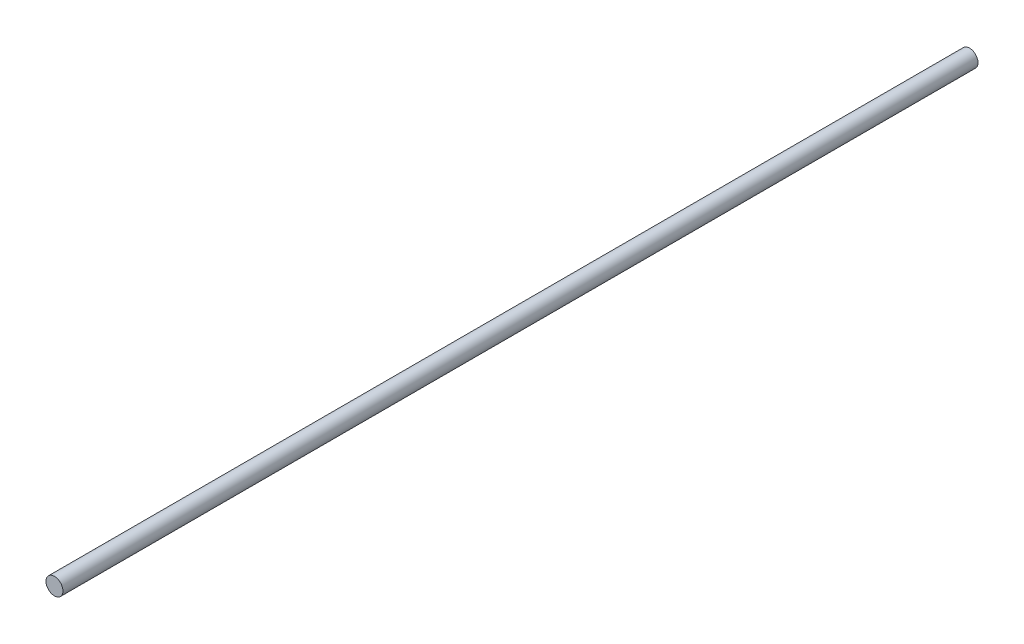
SolidWorks part; units mm, degrees
ref_plane "前视基准面" through (0, 0, 0) normal (0, 0, 1) x (1, 0, 0)
ref_plane "上视基准面" through (0, 0, 0) normal (0, 1, 0) x (1, 0, 0)
ref_plane "右视基准面" through (0, 0, 0) normal (1, 0, 0) x (0, 0, -1)
sketch "草图1" plane through (0, 0, 0) normal (0, 0, 1) x (1, 0, 0)
  circle A0 centre (0, 0) radius 3
  dimension "D1" = 6
extrude "凸台-拉伸1" add sketch "草图1" along normal blind 323.71
